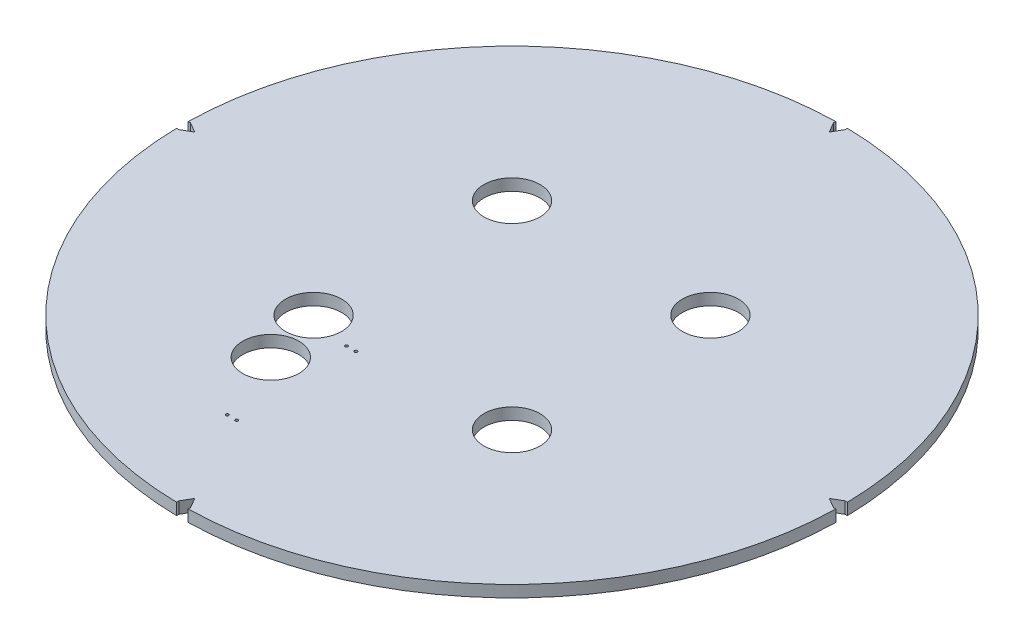
SolidWorks part; units mm, degrees
ref_plane "前视基准面" through (0, 0, 0) normal (0, 0, 1) x (1, 0, 0)
ref_plane "上视基准面" through (0, 0, 0) normal (0, 1, 0) x (1, 0, 0)
ref_plane "右视基准面" through (0, 0, 0) normal (1, 0, 0) x (0, 0, -1)
sketch "草图1" plane through (0, 0, 0) normal (0, 1, 0) x (1, 0, 0)
  circle A0 centre (0, 0) radius 705
  dimension "D1" = 1410
extrude "凸台-拉伸1" add sketch "草图1" along normal blind 25
sketch "草图2" plane through (0, 25, 0) normal (0, 1, 0) x (1, 0, 0)
  line L0 (-12.5, -699.9942) -> (-12.5, -1517.4112) construction
  line L1 (0, -678.3436) -> (-12.5, -699.9942) construction
  line L2 (12.5, -699.9942) -> (0, -678.3436) construction
  line L3 (12.5, -699.9942) -> (12.5, -1517.4112) construction
  line L4 (-12.5, -699.9942) -> (-12.5, -704.8892)
  line L5 (0, -678.3436) -> (-12.5, -699.9942)
  line L6 (12.5, -699.9942) -> (0, -678.3436)
  line L7 (12.5, -699.9942) -> (12.5, -704.8892)
  arc A0 (12.5, -704.8892) -> (-12.5, -704.8892) centre (0, 0) cw
  dimension "D1" = 705
extrude "切除-拉伸1" cut sketch "草图2" against normal up to next
pattern_circular "阵列(圆周)1" count 4 over 360 about axis through (0, 0, 0) along (0, 1, 0) of "切除-拉伸1"
sketch "草图7" plane through (0, 25, 0) normal (0, 1, 0) x (1, 0, 0)
  line L0 (0, 695) -> (0, -695) construction
  line L1 (326.2868, -609.1295) -> (206.0786, -488.9214)
  line L2 (326.2868, -609.1295) -> (467.7082, -467.7082)
  line L3 (467.7082, -467.7082) -> (347.5, -347.5)
  line L4 (206.0786, -488.9214) -> (347.5, -347.5)
  line L5 (326.2868, -609.1295) -> (347.5, -347.5) construction
  line L6 (467.7082, -467.7082) -> (206.0786, -488.9214) construction
  line L7 (-695, 0) -> (695, 0) construction
  line L8 (695, 0) -> (0, -695) construction
  line L9 (491.4392, -491.4392) -> (-491.4392, 491.4392) construction
  line L10 (-612.9008, -323.662) -> (-492.6926, -203.4538)
  line L11 (-612.9008, -323.662) -> (-471.4794, -465.0833)
  line L12 (-471.4794, -465.0833) -> (-351.2713, -344.8752)
  line L13 (-492.6926, -203.4538) -> (-351.2713, -344.8752)
  line L14 (-612.9008, -323.662) -> (-351.2713, -344.8752) construction
  line L15 (-471.4794, -465.0833) -> (-492.6926, -203.4538) construction
  line L16 (-332.2351, 613.6048) -> (-212.027, 493.3967)
  line L17 (-332.2351, 613.6048) -> (-473.6565, 472.1835)
  line L18 (-473.6565, 472.1835) -> (-353.4483, 351.9753)
  line L19 (-212.027, 493.3967) -> (-353.4483, 351.9753)
  line L20 (-332.2351, 613.6048) -> (-353.4483, 351.9753) construction
  line L21 (-473.6565, 472.1835) -> (-212.027, 493.3967) construction
  line L22 (605.0317, 332.9392) -> (484.8235, 212.731)
  line L23 (605.0317, 332.9392) -> (463.6103, 474.3606)
  line L24 (463.6103, 474.3606) -> (343.4022, 354.1524)
  line L25 (484.8235, 212.731) -> (343.4022, 354.1524)
  line L26 (605.0317, 332.9392) -> (343.4022, 354.1524) construction
  line L27 (463.6103, 474.3606) -> (484.8235, 212.731) construction
  line L28 (347.5, -347.5) -> (347.5, 0) construction
  circle A0 centre (0, 0) radius 695
  arc A1 (467.7082, -467.7082) -> (347.5, -347.5) centre (407.6041, -407.6041) ccw
  arc A2 (-471.4794, -465.0833) -> (-351.2713, -344.8752) centre (-411.3753, -404.9792) ccw
  arc A3 (-473.6565, 472.1835) -> (-353.4483, 351.9753) centre (-413.5524, 412.0794) ccw
  arc A4 (463.6103, 474.3606) -> (343.4022, 354.1524) centre (403.5062, 414.2565) ccw
  point P2 (336.8934, -478.3148)
  point P14 (-482.086, -334.2686)
  point P20 (-342.8417, 482.7901)
  point P26 (474.2169, 343.5458)
  point P35 (20.5792, -31.4481)
  dimension "D1" = 1390
  dimension "D2" = 200
  dimension "D3" = 170
sketch "草图8" plane through (0, 25, 0) normal (0, 1, 0) x (1, 0, 0)
  line L0 (491.4392, -491.4392) -> (-491.4392, 491.4392) construction
  circle A0 centre (212.132, -212.132) radius 60
  circle A1 centre (-212.132, -212.132) radius 60
  circle A2 centre (-212.132, 212.132) radius 60
  circle A3 centre (212.132, 212.132) radius 60
  point P13 (0, 0)
  dimension "D3" = 120
  dimension "D2" = 300
  dimension "D1" = 4
extrude "切除-拉伸2" cut sketch "草图8" against normal up to next
sketch "草图9" plane through (0, 25, 0) normal (0, 1, 0) x (1, 0, 0)
  line L0 (-82.9781, -126.8961) -> (-50.0682, -138.8099) construction
  line L1 (-82.9781, -126.8961) -> (-50.0682, -138.8099)
sketch "草图10" plane through (0, 25, 0) normal (0, 1, 0) x (1, 0, 0)
  line L0 (-82.9781, -126.8961) -> (-50.0682, -138.8099) construction
  line L1 (-82.9781, -126.8961) -> (-50.0682, -138.8099)
  line L2 (-50.0682, -138.8099) -> (-58.576, -162.3114)
  line L3 (-58.576, -162.3114) -> (-91.4859, -150.3976)
  line L4 (-91.4859, -150.3976) -> (-82.9781, -126.8961)
sketch "草图11" plane through (0, 25, 0) normal (0, 1, 0) x (1, 0, 0)
  line L1 (-36.1645, -101.1698) -> (-68.9964, -89.0426) construction
  line L2 (-73.37, -151.3894) -> (-52.5805, -95.1062) construction
  circle A0 centre (-73.37, -151.3894) radius 60
extrude "切除-拉伸3" cut sketch "草图11" against normal blind 100
sketch "草图12" plane through (0, 25, 0) normal (0, 1, 0) x (1, 0, 0)
  circle A0 centre (-73.37, -151.3894) radius 60 construction
  circle A1 centre (-73.37, -151.3894) radius 60
extrude "凸台-拉伸2" add sketch "草图12" against normal up to surface (25 mm away) up to face at (-73.37, 0, 211.3894)
sketch "草图13" plane through (0, 25, 0) normal (0, 1, 0) x (1, 0, 0)
  circle A0 centre (-179.9936, -335.7653) radius 60 construction
  circle A1 centre (-179.9936, -335.7653) radius 60
extrude "切除-拉伸4" cut sketch "草图13" against normal through all
sketch "草图15" plane through (0, 25, 0) normal (0, 1, 0) x (1, 0, 0)
  line L0 (-179.9936, -335.7653) -> (-109.9936, -335.7653) construction
  line L1 (-109.9936, -335.7653) -> (-109.9936, -233.7653)
  line L2 (-109.9936, -335.7653) -> (-109.9936, -488.7653)
  line L3 (-109.9936, -233.7653) -> (-99.9936, -233.7653)
  line L4 (-109.9936, -488.7653) -> (-99.9936, -488.7653)
  circle A0 centre (-99.9936, -233.7653) radius 3
  circle A1 centre (-99.9936, -488.7653) radius 3
  circle A2 centre (-119.9936, -233.7653) radius 3
  circle A3 centre (-119.9936, -488.7653) radius 3
extrude "切除-拉伸5" cut sketch "草图15" against normal through all
